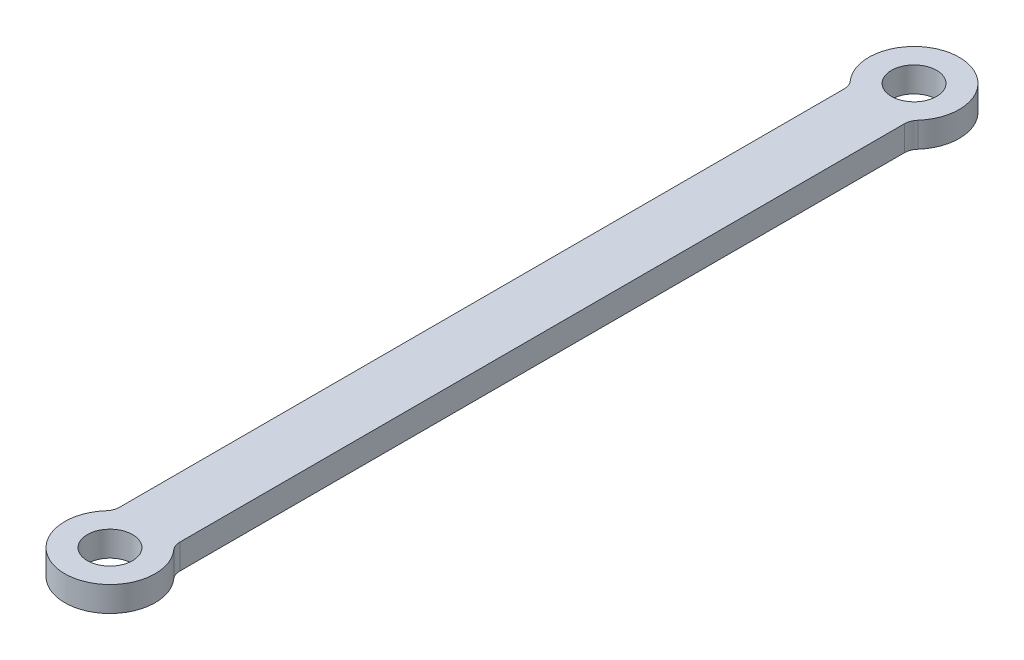
SolidWorks part; units mm, degrees
ref_plane "前视基准面" through (0, 0, 0) normal (0, 0, 1) x (1, 0, 0)
ref_plane "上视基准面" through (0, 0, 0) normal (0, 1, 0) x (1, 0, 0)
ref_plane "右视基准面" through (0, 0, 0) normal (1, 0, 0) x (0, 0, -1)
sketch "草图1" plane through (0, 0, 0) normal (0, 1, 0) x (1, 0, 0)
  line L0 (-81.8898, 37.732) -> (-81.8898, -106.3935)
  line L5 (-69.8898, 37.732) -> (-69.8898, -106.3935)
  arc A0 (-69.1398, 39.7164) -> (-82.6398, 39.7164) centre (-75.8898, 45.6693) ccw
  arc A1 (-82.6398, -108.3778) -> (-69.1398, -108.3778) centre (-75.8898, -114.3307) ccw
  circle A2 centre (-75.8898, 45.6693) radius 4.5
  circle A3 centre (-75.8898, -114.3307) radius 4.5
  arc A4 (-69.1398, -108.3778) -> (-69.8898, -106.3935) centre (-66.8898, -106.3935) cw
  arc A5 (-81.8898, -106.3935) -> (-82.6398, -108.3778) centre (-84.8898, -106.3935) cw
  arc A6 (-81.8898, 37.732) -> (-82.6398, 39.7164) centre (-84.8898, 37.732) ccw
  arc A7 (-69.8898, 37.732) -> (-69.1398, 39.7164) centre (-66.8898, 37.732) cw
  point P0 (0, 0)
  dimension "D1" = 3
  dimension "D2" = 3
  dimension "D3" = 3
  dimension "D4" = 3
extrude "凸台-拉伸1" add sketch "草图1" along normal blind 5
